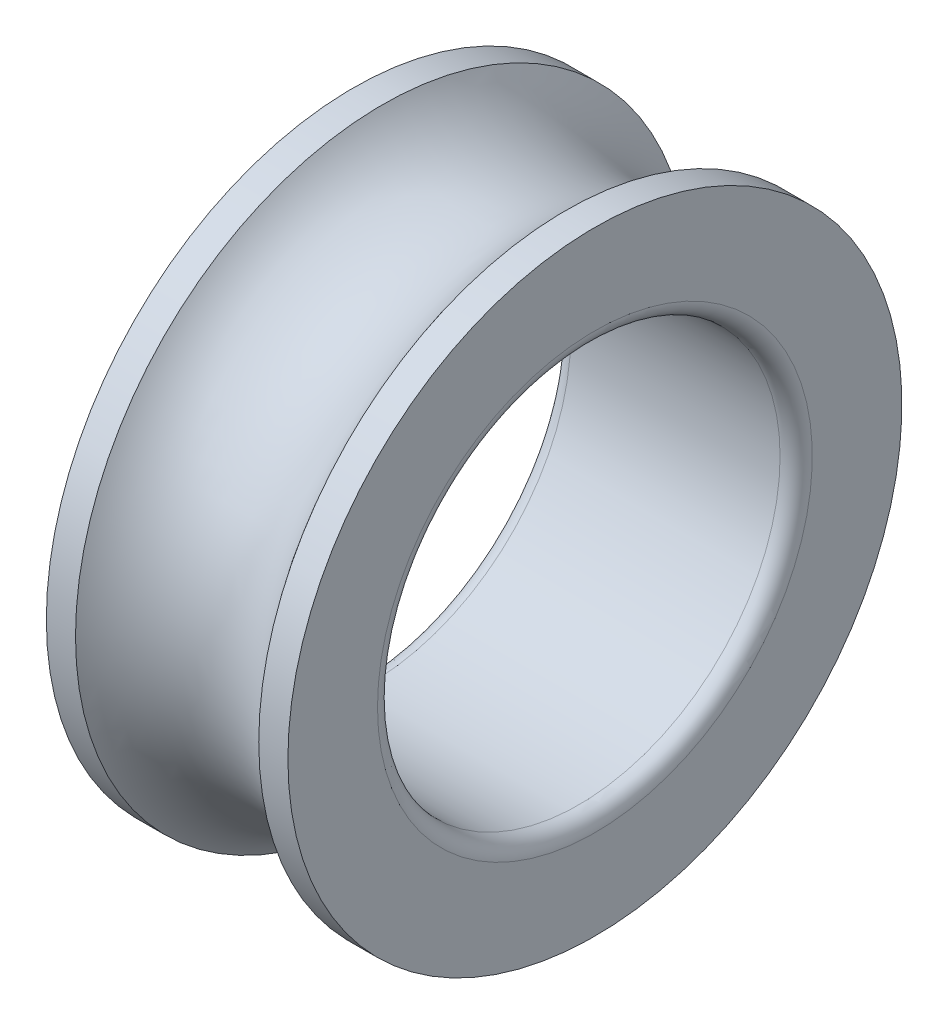
SolidWorks part; units mm, degrees
ref_plane "Front Plane" through (0, 0, 0) normal (0, 0, 1) x (1, 0, 0)
ref_plane "Top Plane" through (0, 0, 0) normal (0, 1, 0) x (1, 0, 0)
ref_plane "Right Plane" through (0, 0, 0) normal (1, 0, 0) x (0, 0, -1)
sketch "Sketch1" plane through (0, 0, 0) normal (0, 0, 1) x (1, 0, 0)
  line L0 (-18.9011, 0) -> (36.6911, 0) construction
  line L1 (17.0682, 57.19) -> (22.5, 57.19)
  line L2 (-19.5, 37.5) -> (19.5, 37.5)
  line L3 (-22.5, 40.5) -> (-22.5, 57.19)
  line L4 (-22.5, 57.19) -> (-17.0682, 57.19)
  line L5 (22.5, 40.5) -> (22.5, 57.19)
  line L6 (-22.5, 37.5) -> (22.5, 57.19) construction
  line L7 (-22.5, 57.19) -> (22.5, 37.5) construction
  arc A0 (17.0682, 57.19) -> (-17.0682, 57.19) centre (0, 68.99) cw
  arc A1 (19.5, 37.5) -> (22.5, 40.5) centre (19.5, 40.5) ccw
  arc A2 (-19.5, 37.5) -> (-22.5, 40.5) centre (-19.5, 40.5) cw
  point P3 (0, 47.345)
  dimension "D5" = 20.75
  dimension "D6" = 3
  dimension "D1" = 45
  dimension "D2" = 37.5
  dimension "D3" = 57.19
  dimension "D4" = 11.8
revolve "Revolve1" add sketch "Sketch1" angle 360 about L0
